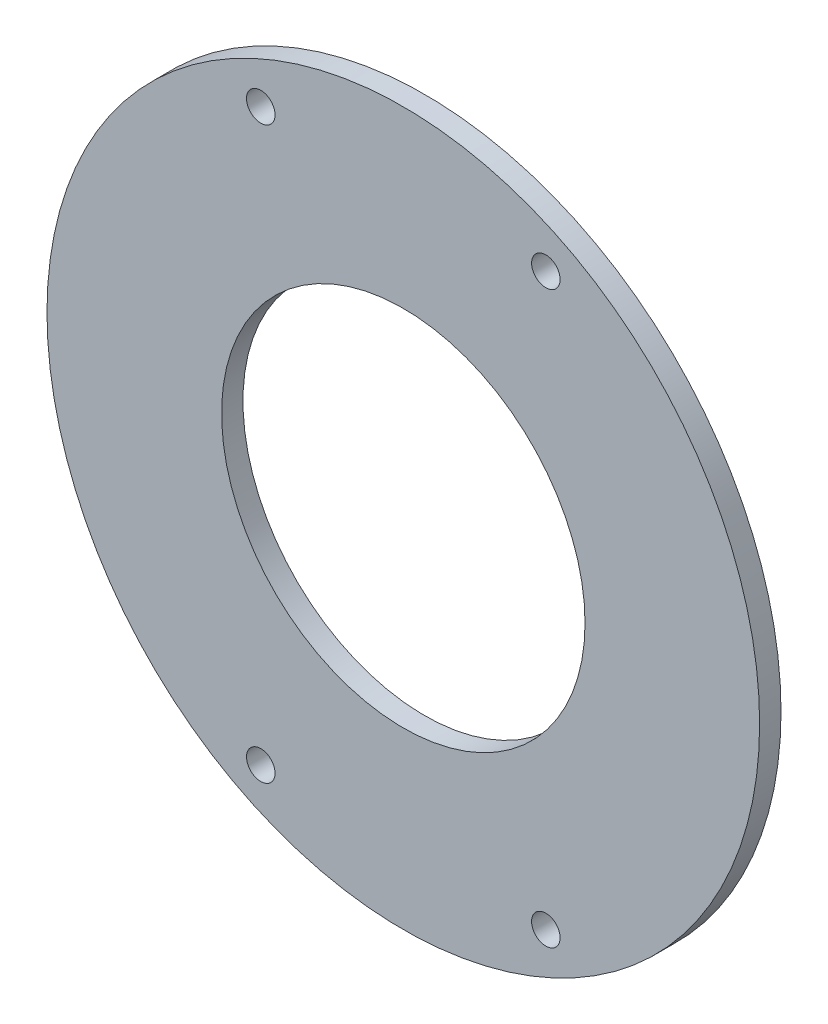
SolidWorks part; units mm, degrees
ref_plane "前视基准面" through (0, 0, 0) normal (0, 0, 1) x (1, 0, 0)
ref_plane "上视基准面" through (0, 0, 0) normal (0, 1, 0) x (1, 0, 0)
ref_plane "右视基准面" through (0, 0, 0) normal (1, 0, 0) x (0, 0, -1)
sketch "草图1" plane through (0, 0, 0) normal (0, 0, 1) x (1, 0, 0)
  line L0 (0, -1.8543) -> (0, -21.8543) construction
  line L1 (0, -21.8543) -> (-20, -21.8543) construction
  line L2 (0, -1.8543) -> (0, 64.1457) construction
  circle A0 centre (0, -1.8543) radius 10 construction
  circle A1 centre (0, -21.8543) radius 4.5 construction
  circle A2 centre (-20, -21.8543) radius 2 construction
  circle A3 centre (-20, 18.1457) radius 2
  circle A4 centre (20, 18.1457) radius 2
  circle A5 centre (20, -21.8543) radius 2 construction
  circle A6 centre (20, -61.8543) radius 2
  circle A7 centre (-20, -61.8543) radius 2
  circle A8 centre (0, -21.8543) radius 25.5
  circle A9 centre (0, -21.8543) radius 50
  point P21 (-19.9058, 17.0924)
  point P22 (38.7958, -18.5664)
  dimension "D1" = 4
  dimension "D4" = 51
  dimension "D2" = 40
  dimension "D3" = 80
extrude "凸台-拉伸1" add sketch "草图1" along normal blind 3 contours A8
